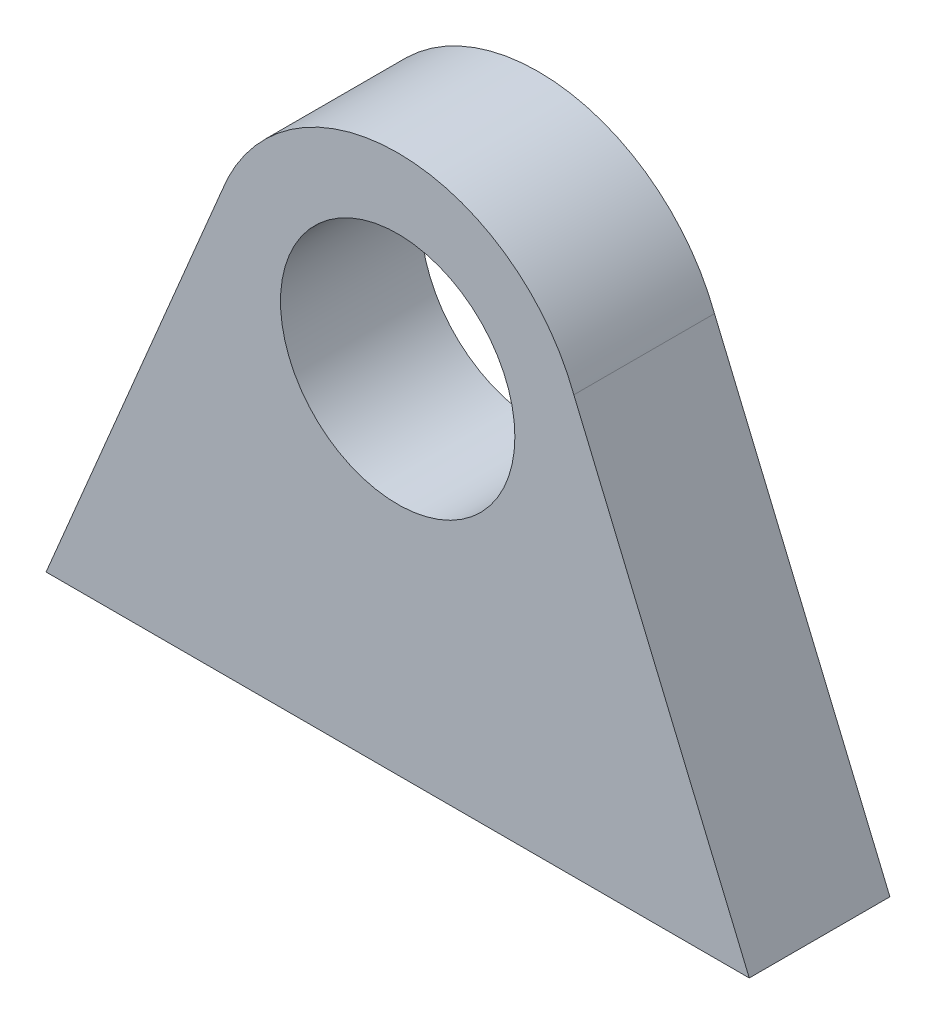
SolidWorks part; units mm, degrees
ref_plane "Front Plane" through (0, 0, 0) normal (0, 0, 1) x (1, 0, 0)
ref_plane "Top Plane" through (0, 0, 0) normal (0, 1, 0) x (1, 0, 0)
ref_plane "Right Plane" through (0, 0, 0) normal (1, 0, 0) x (0, 0, -1)
sketch "Sketch1" plane through (0, 0, 0) normal (0, 0, 1) x (1, 0, 0)
  line L0 (0, 0) -> (37.4403, 89.067)
  line L1 (0, 0) -> (150, 0)
  line L5 (150, 0) -> (112.5772, 89.0253)
  circle A0 centre (75, 75) radius 25
  arc A1 (37.4403, 89.067) -> (112.5772, 89.0253) centre (75.0008, 74.7626) cw
  dimension "D3" = 50
  dimension "Length" = 150
  dimension "Width" = 75
  dimension "D7" = 67.2
  dimension "D8" = 67.2
extrude "Extrude1" add sketch "Sketch1" along normal blind 30
